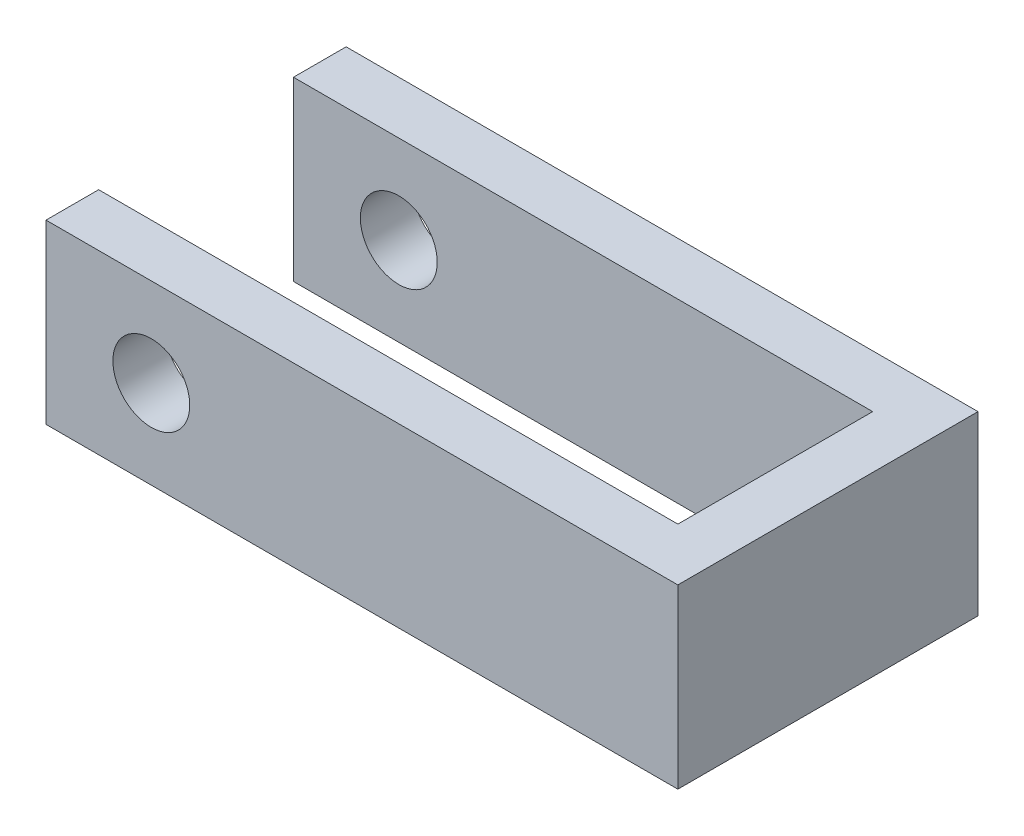
SolidWorks part; units mm, degrees
ref_plane "Front Plane" through (0, 0, 0) normal (0, 0, 1) x (1, 0, 0)
ref_plane "Top Plane" through (0, 0, 0) normal (0, 1, 0) x (1, 0, 0)
ref_plane "Right Plane" through (0, 0, 0) normal (1, 0, 0) x (0, 0, -1)
sketch "Sketch1" plane through (0, 0, 0) normal (0, 1, 0) x (1, 0, 0)
  line L0 (-2.5, 9.25) -> (-2.5, 4.25)
  line L1 (2.5, -9.25) -> (-2.5, -9.25)
  line L2 (2.5, -9.25) -> (2.5, 9.25)
  line L3 (2.5, 9.25) -> (-2.5, 9.25)
  line L4 (-2.5, -9.25) -> (-2.5, 9.25)
  line L5 (2.5, -9.25) -> (-2.5, 9.25) construction
  line L6 (2.5, 9.25) -> (-2.5, -9.25) construction
  line L7 (2.5, 9.25) -> (-57.5, 9.25)
  line L8 (2.5, 9.25) -> (2.5, 14.25)
  line L9 (-57.5, 9.25) -> (-57.5, 14.25)
  line L10 (0, 0) -> (-57.5, 0) construction
  line L11 (2.5, 14.25) -> (-57.5, 14.25)
  line L12 (2.5, -9.25) -> (2.5, -14.25)
  line L13 (-57.5, -9.25) -> (-57.5, -14.25)
  line L14 (2.5, -14.25) -> (-57.5, -14.25)
  line L15 (2.5, -9.25) -> (-57.5, -9.25)
  point P0 (0, 0)
  dimension "D1" = 18.5
  dimension "D2" = 5
  dimension "D3" = 60
  dimension "D4" = 5
extrude "Boss-Extrude2" add sketch "Sketch1" against normal blind 16.8 contours L1 L15 L13 L14 L12 | L4 L1 L2 L3 L0 | L8 L11 L9 L7 L3
sketch "Sketch5" plane through (0, 0, 14.25) normal (0, 0, 1) x (1, 0, 0)
  line L0 (-57.5, -8.4) -> (2.5, -8.4) construction
  line L1 (-57.5, -16.8) -> (-57.5, 0) construction
  line L2 (2.5, -16.8) -> (2.5, 0) construction
  circle A0 centre (-47.5, -8.4) radius 3.65
  dimension "D1" = 7.3
  dimension "D2" = 10
extrude "Cut-Extrude3" cut sketch "Sketch5" against normal blind 28.5
